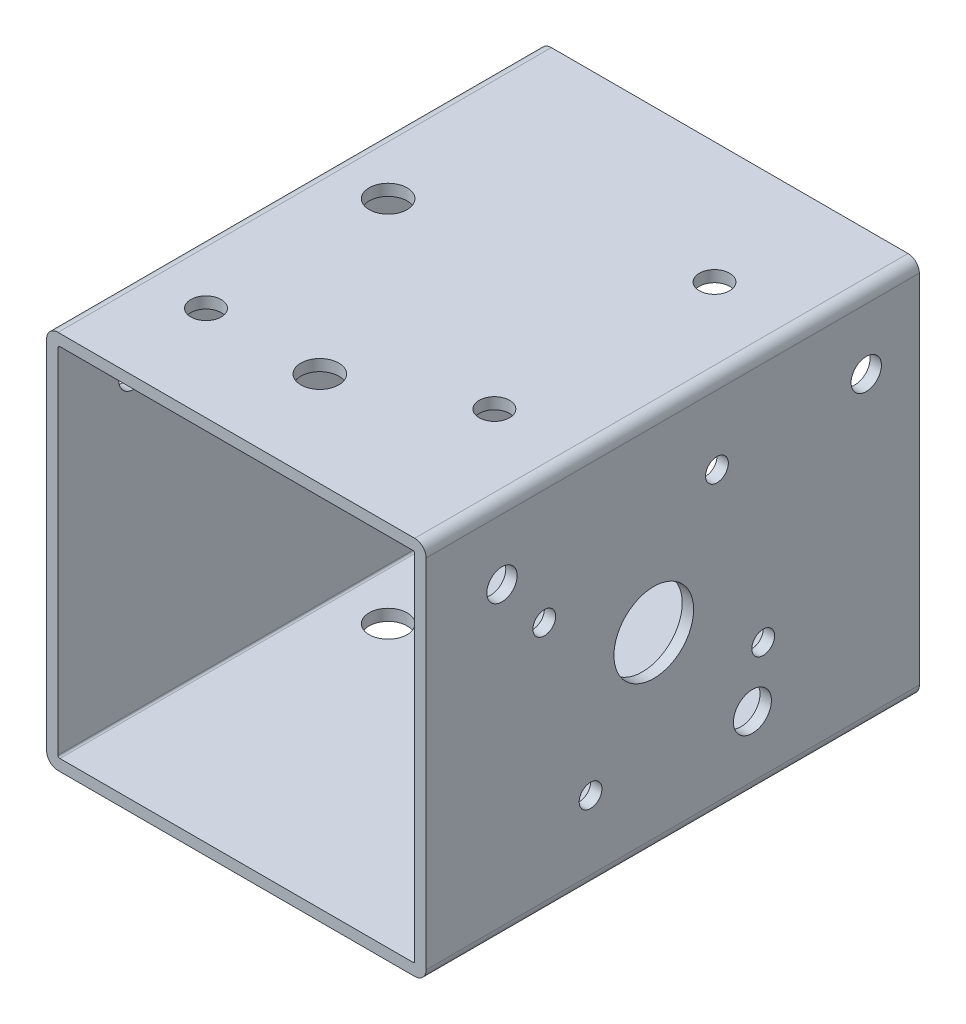
SolidWorks part; units mm, degrees
ref_plane "Front Plane" through (0, 0, 0) normal (0, 0, 1) x (1, 0, 0)
ref_plane "Top Plane" through (0, 0, 0) normal (0, 1, 0) x (1, 0, 0)
ref_plane "Right Plane" through (0, 0, 0) normal (1, 0, 0) x (0, 0, -1)
sketch "Sketch1" plane through (0, 0, 0) normal (0, 0, 1) x (1, 0, 0)
  line L1 (-50, 50) -> (50, 50)
  line L2 (-50, 50) -> (-50, -50)
  line L3 (-50, -50) -> (50, -50)
  line L4 (50, 50) -> (50, -50)
  line L5 (-50, 50) -> (50, -50) construction
  line L6 (-50, -50) -> (50, 50) construction
  point P0 (0, 0)
  dimension "D1" = 100
  dimension "D2" = 100
extrude "Extrude-Thin1" add sketch "Sketch1" along normal blind 130 thin
fillet "Fillet1" radius 0.5 4 edges at (-47, -47, 65) (-47, 47, 65) (47, 47, 65) (47, -47, 65)
fillet "Fillet2" radius 3 4 edges at (50, -50, 65) (-50, -50, 65) (50, 50, 65) (-50, 50, 65)
sketch "Holes - top" plane through (0, 0, 0) normal (0, 1, 0) x (1, 0, 0)
  line L0 (-3, 0) -> (-3, -130) construction
  line L1 (47, -130) -> (-47, -130) construction
  line L2 (-23, 0) -> (-23, -130) construction
  line L3 (47, 0) -> (-47, 0) construction
  line L4 (17, 0) -> (17, -130) construction
  circle A0 centre (-34, -56) radius 11 construction
  circle A1 centre (28, -90) radius 11 construction
  circle A2 centre (28, -32) radius 11 construction
  dimension "D4" = 22
  dimension "D1" = 40
  dimension "D2" = 40
  dimension "D3" = 32
  dimension "D5" = 56
  dimension "D6" = 3
hole_wizard "Ø8.0 (8) Diameter Hole2" positions "Sketch6" profile "Sketch5" hole size "Ø8.0" standard "ANSI Metric" end condition through all
sketch "Sketch6" plane through (0, 50, 0) normal (0, 1, 0) x (1, 0, 0)
  point P0 (28, -32)
  point P6 (28, -90)
sketch "Sketch5" plane through (28, 50, 32) normal (1, 0, 0) x (0, 0, 1)
  line L0 (0, 0) -> (0, 100)
  line L1 (0, 100) -> (4, 100)
  line L2 (4, 100) -> (4, 0)
  line L5 (4, 0) -> (0, 0)
  line L11 (0, -6.35) -> (0, 107.95) construction
  dimension "Thru Hole Dia." = 8
  dimension "Thru Hole Depth" = 100
sketch "Holes - side" plane through (0, 0, 0) normal (1, 0, 0) x (0, 0, -1)
  line L0 (0, 0) -> (-130, 0) construction
  line L1 (-130, -47) -> (-130, 47) construction
  line L2 (-130, 20) -> (0, 20) construction
  line L3 (0, -47) -> (0, 47) construction
  line L4 (-130, -20) -> (0, -20) construction
  circle A0 centre (-110, 31) radius 11 construction
  circle A1 centre (-14, 31) radius 11 construction
  circle A2 centre (-44, -31) radius 11 construction
  dimension "D1" = 40
  dimension "D2" = 22
  dimension "D3" = 20
  dimension "D4" = 14
  dimension "D5" = 44
hole_wizard "Ø8.0 (8) Diameter Hole3" positions "Sketch9" profile "Sketch8" hole size "Ø8.0" standard "ANSI Metric" end condition through all
sketch "Sketch9" plane through (50, 0, 0) normal (1, 0, 0) x (0, 0, -1)
  point P0 (-14, 31)
  point P3 (-110, 31)
sketch "Sketch8" plane through (50, 31, 14) normal (0, 1, 0) x (0, 0, -1)
  line L0 (0, 0) -> (0, 100)
  line L1 (0, 100) -> (4, 100)
  line L2 (4, 100) -> (4, 0)
  line L5 (4, 0) -> (0, 0)
  line L11 (0, -6.35) -> (0, 107.95) construction
  dimension "Thru Hole Dia." = 8
  dimension "Thru Hole Depth" = 100
hole_wizard "Ø10.0 (10) Diameter Hole1" positions "Sketch12" profile "Sketch11" hole size "Ø10.0" standard "ANSI Metric" end condition through all
sketch "Sketch12" plane through (0, 50, 0) normal (0, 1, 0) x (1, 0, 0)
  point P0 (-34, -56)
sketch "Sketch11" plane through (-34, 50, 56) normal (1, 0, 0) x (0, 0, 1)
  line L0 (0, 0) -> (0, 100)
  line L1 (0, 100) -> (5, 100)
  line L2 (5, 100) -> (5, 0)
  line L5 (5, 0) -> (0, 0)
  line L11 (0, -6.35) -> (0, 107.95) construction
  dimension "Thru Hole Dia." = 10
  dimension "Thru Hole Depth" = 100
hole_wizard "Ø10.0 (10) Diameter Hole2" positions "Sketch14" profile "Sketch13" hole size "Ø10.0" standard "ANSI Metric" end condition through all
sketch "Sketch14" plane through (50, 0, 0) normal (1, 0, 0) x (0, 0, -1)
  point P0 (-44, -31)
sketch "Sketch13" plane through (50, -31, 44) normal (0, 1, 0) x (0, 0, -1)
  line L0 (0, 0) -> (0, 100)
  line L1 (0, 100) -> (5, 100)
  line L2 (5, 100) -> (5, 0)
  line L5 (5, 0) -> (0, 0)
  line L11 (0, -6.35) -> (0, 107.95) construction
  dimension "Thru Hole Dia." = 10
  dimension "Thru Hole Depth" = 100
hole_wizard "M8x1.25 Tapped Hole1" positions "Sketch18" profile "Sketch17" tap size "M8x1.25" standard "ANSI Metric"
sketch "Sketch18" plane through (-50, 0, 0) normal (-1, 0, 0) x (0, 0, 1)
  line L0 (56, 35) -> (56, -15) construction
  point P0 (56, -15)
  point P2 (56, 35)
  dimension "D1" = 56
  dimension "D2" = 35
  dimension "D3" = 15
sketch "Sketch17" plane through (-50, -15, 56) normal (0, 1, 0) x (0, 0, 1)
  line L0 (0, 0) -> (0, 3)
  line L1 (0, 3) -> (3.4, 3)
  line L2 (3.4, 3) -> (3.4, 0)
  line L5 (3.4, 0) -> (0, 0)
  line L11 (0, -6.35) -> (0, 107.95) construction
  dimension "Thru Tap Drill Dia." = 6.8
  dimension "Thru Tap Drill Depth" = 3
cosmetic thread "Hole Thread1" parameters "D2"=8
cosmetic thread "Hole Thread2" parameters "D2"=8
hole_wizard "M8x1.25 Tapped Hole2" positions "Sketch21" profile "Sketch20" tap size "M8x1.25" standard "ANSI Metric"
sketch "Sketch21" plane through (0, -50, 0) normal (0, -1, 0) x (-1, 0, 0)
  line L0 (20, -44) -> (-35, -44) construction
  point P0 (20, -44)
  point P2 (-35, -44)
  dimension "D1" = 44
  dimension "D2" = 35
  dimension "D3" = 20
sketch "Sketch20" plane through (-20, -50, 44) normal (1, 0, 0) x (0, 0, -1)
  line L0 (0, 0) -> (0, 3)
  line L1 (0, 3) -> (3.4, 3)
  line L2 (3.4, 3) -> (3.4, 0)
  line L5 (3.4, 0) -> (0, 0)
  line L11 (0, -6.35) -> (0, 107.95) construction
  dimension "Thru Tap Drill Dia." = 6.8
  dimension "Thru Tap Drill Depth" = 3
cosmetic thread "Hole Thread3" parameters "D2"=8
cosmetic thread "Hole Thread4" parameters "D2"=8
sketch "Holes - Nema 23 motor" plane through (0, 0, 0) normal (1, 0, 0) x (0, 0, -1)
  line L0 (-98.8427, 16.6524) -> (-53.3476, 28.8427) construction
  line L1 (-98.8427, 16.6524) -> (-86.6524, -28.8427) construction
  line L2 (-53.3476, 28.8427) -> (-41.1573, -16.6524) construction
  line L3 (-86.6524, -28.8427) -> (-41.1573, -16.6524) construction
  line L4 (-98.8427, 16.6524) -> (-41.1573, -16.6524) construction
  line L5 (-53.3476, 28.8427) -> (-86.6524, -28.8427) construction
  line L6 (0, 0) -> (-130, 0) construction
  point P1 (-70, 0)
  dimension "D1" = 70
  dimension "D2" = 47.1
  dimension "D3" = 47.1
  dimension "D4" = 15
hole_wizard "Ø21.0 (21) Diameter Hole1" positions "Sketch24" profile "Sketch23" hole size "Ø21.0" standard "ANSI Metric"
sketch "Sketch24" plane through (50, 0, 0) normal (1, 0, 0) x (0, 0, -1)
  point P0 (-70, 0)
sketch "Sketch23" plane through (50, 0, 70) normal (0, 1, 0) x (0, 0, -1)
  line L0 (0, 0) -> (0, 3)
  line L1 (0, 3) -> (10.5, 3)
  line L2 (10.5, 3) -> (10.5, 0)
  line L5 (10.5, 0) -> (0, 0)
  line L11 (0, -6.35) -> (0, 107.95) construction
  dimension "Thru Hole Dia." = 21
  dimension "Thru Hole Depth" = 3
hole_wizard "Ø6.0 (6) Diameter Hole1" positions "Sketch26" profile "Sketch25" hole size "Ø6.0" standard "ANSI Metric"
sketch "Sketch26" plane through (50, 0, 0) normal (1, 0, 0) x (0, 0, -1)
  point P0 (-41.1573, -16.6524)
  point P3 (-53.3476, 28.8427)
  point P6 (-98.8427, 16.6524)
  point P9 (-86.6524, -28.8427)
sketch "Sketch25" plane through (50, -16.6524, 41.1573) normal (0, 1, 0) x (0, 0, -1)
  line L0 (0, 0) -> (0, 3)
  line L1 (0, 3) -> (3, 3)
  line L2 (3, 3) -> (3, 0)
  line L5 (3, 0) -> (0, 0)
  line L11 (0, -6.35) -> (0, 107.95) construction
  dimension "Thru Hole Dia." = 6
  dimension "Thru Hole Depth" = 3
hole_wizard "Ø10.0 (10) Diameter Hole4" positions "Sketch29" profile "Sketch28" hole size "Ø10.0" standard "ANSI Metric"
sketch "Sketch29" plane through (0, 50, 0) normal (0, 1, 0) x (1, 0, 0)
  line L0 (-3, 0) -> (-3, -130) construction
  point P0 (-3, -105)
  dimension "D1" = 15
sketch "Sketch28" plane through (-3, 50, 105) normal (1, 0, 0) x (0, 0, 1)
  line L0 (0, 0) -> (0, 3)
  line L1 (0, 3) -> (5, 3)
  line L2 (5, 3) -> (5, 0)
  line L5 (5, 0) -> (0, 0)
  line L11 (0, -6.35) -> (0, 107.95) construction
  dimension "Thru Hole Dia." = 10
  dimension "Thru Hole Depth" = 3
sketch "Sketch32" plane through (50, 0, 0) normal (1, 0, 0) x (0, 0, -1)
  line L1 (0, -47) -> (0, 47) construction
  line L2 (-65, 69.5535) -> (-65, -72.7704) construction
  line L3 (-130, -47) -> (-130, 47) construction
  line L4 (-130, 50) -> (0, 50) construction
  circle A0 centre (-5, 13) radius 2
  circle A1 centre (-5, 4) radius 2
  circle A2 centre (-125, 4) radius 2
  circle A3 centre (-125, 13) radius 2
  dimension "D1" = 46
  dimension "D2" = 9
  dimension "D3" = 4
  dimension "D5" = 5
  dimension "D4" = 0
  dimension "D6" = 65
sketch "Sketch33" plane through (0, 50, 0) normal (0, 1, 0) x (1, 0, 0)
  circle A0 centre (-33, -105) radius 4
  circle A1 centre (-33, -105) radius 4 construction
extrude "Cut-Extrude1" cut sketch "Sketch33" against normal blind 10
equation "\"a\"= \"Trolley Profile@Plasma Beta.Assembly\""
equation "\"b\"= \"Trolley Profile Thickness@Plasma Beta.Assembly\""
equation "\"L\"= 130"
equation "\"D2@Sketch1\"=\"a\""
equation "\"D1@Sketch1\"=\"a\""
equation "\"D1@Extrude-Thin1\"=\"L\""
equation "\"D5@Extrude-Thin1\"=\"b\""
equation "\"D1@Fillet2\"=\"b\""
equation "\"d-bearing\"= 22'diameter of bearing"
equation "\"a-small\"= \"Beam Profile@Plasma Beta.Assembly\"'profile of smaller beam"
equation "\"D4@Holes - top\"=\"d-bearing\""
equation "\"D2@Holes - side\"=\"d-bearing\""
equation "\"D1@Holes - top\"=\"a-small\""
equation "\"D1@Holes - side\"=\"a-small\""
